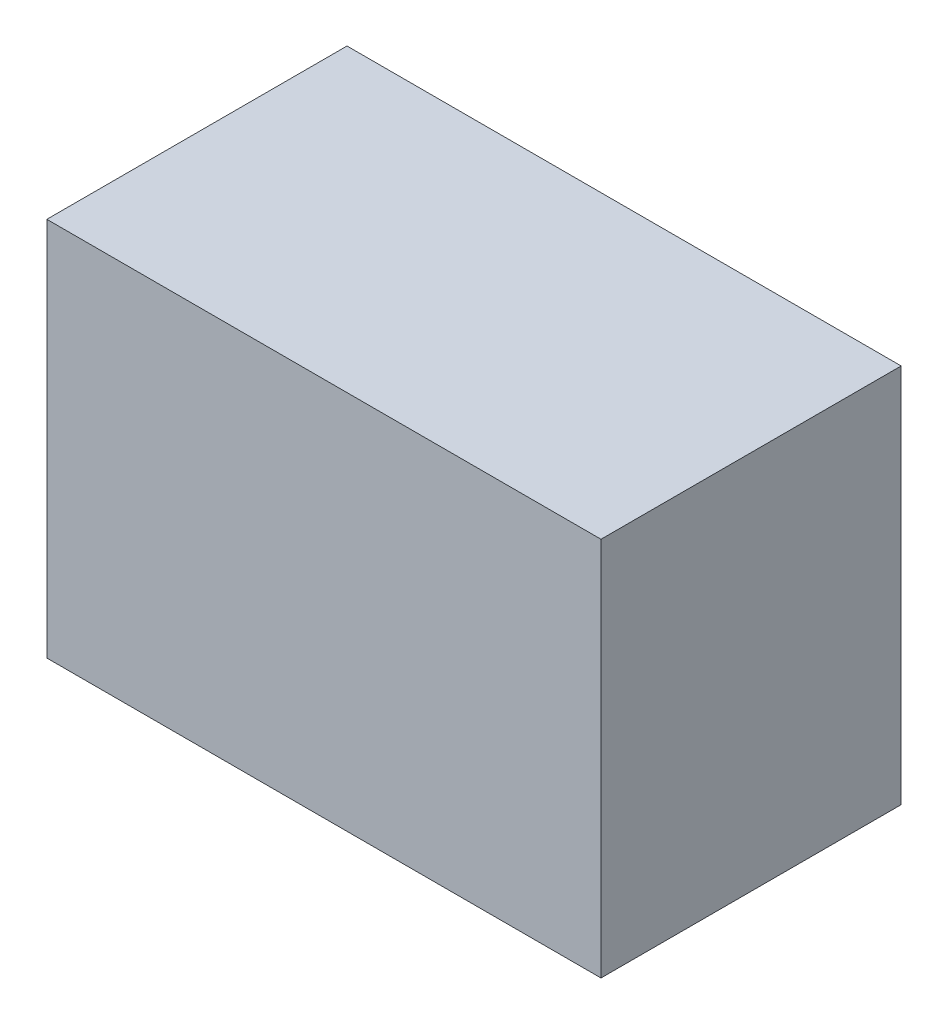
SolidWorks part; units mm, degrees
ref_plane "Front Plane" through (0, 0, 0) normal (0, 0, 1) x (1, 0, 0)
ref_plane "Top Plane" through (0, 0, 0) normal (0, 1, 0) x (1, 0, 0)
ref_plane "Right Plane" through (0, 0, 0) normal (1, 0, 0) x (0, 0, -1)
sketch "Sketch1" plane through (0, 0, 0) normal (0, 1, 0) x (1, 0, 0)
  line L1 (0, 0) -> (304.8, 0)
  line L2 (0, 0) -> (0, 165.1)
  line L3 (0, 165.1) -> (304.8, 165.1)
  line L4 (304.8, 0) -> (304.8, 165.1)
  dimension "D1" = 304.8
  dimension "D2" = 165.1
extrude "Boss-Extrude1" add sketch "Sketch1" along normal blind 209
